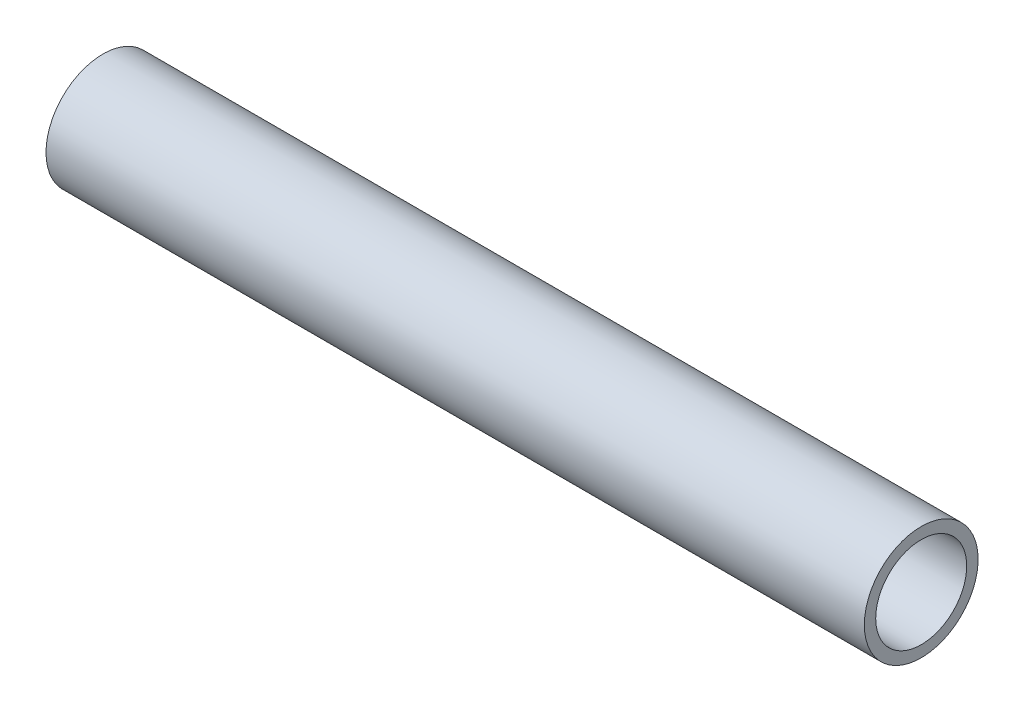
SolidWorks part; units mm, degrees
material "PC High Viscosity"
ref_plane "Front Plane" through (0, 0, 0) normal (0, 0, 1) x (1, 0, 0)
ref_plane "Top Plane" through (0, 0, 0) normal (0, 1, 0) x (1, 0, 0)
ref_plane "Right Plane" through (0, 0, 0) normal (1, 0, 0) x (0, 0, -1)
sketch "Sketch1" plane through (0, 0, 0) normal (1, 0, 0) x (0, 0, -1)
  circle A0 centre (0, 0) radius 15.875
  dimension "D1" = 31.75
extrude "Extrude-Thin1" add sketch "Sketch1" along normal mid plane 228.346 thin thin type one direction reverse wall 3.175
